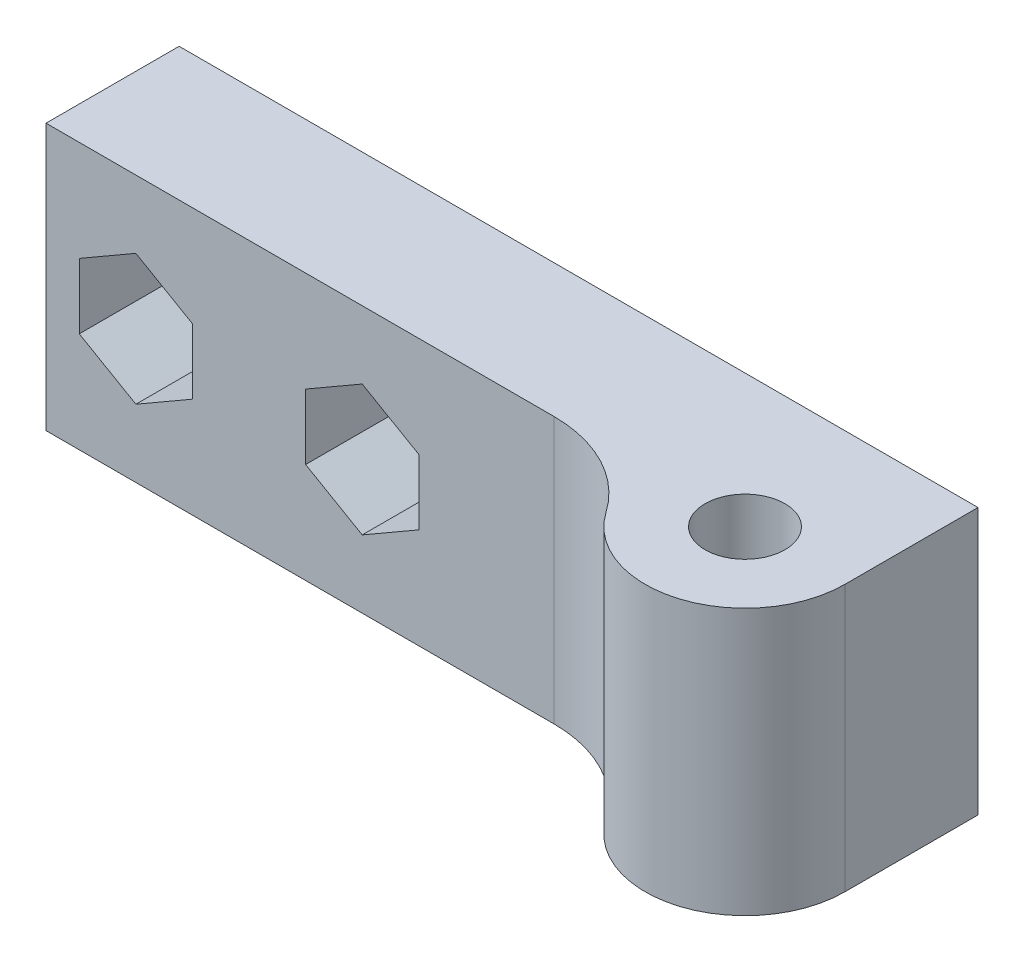
SolidWorks part; units mm, degrees
ref_plane "Front Plane" through (0, 0, 0) normal (0, 0, 1) x (1, 0, 0)
ref_plane "Top Plane" through (0, 0, 0) normal (0, 1, 0) x (1, 0, 0)
ref_plane "Right Plane" through (0, 0, 0) normal (1, 0, 0) x (0, 0, -1)
sketch "Sketch1" plane through (0, 0, 0) normal (0, 0, 1) x (1, 0, 0)
  line L1 (-30, 0) -> (30, 0)
  line L2 (-30, 0) -> (-30, -20)
  line L3 (-30, -20) -> (30, -20)
  line L4 (30, 0) -> (30, -20)
  point P4 (0, 0)
  dimension "D1" = 60
  dimension "D2" = 20
extrude "Boss-Extrude1" add sketch "Sketch1" along normal blind 10
sketch "Sketch2" plane through (0, 0, 10) normal (0, 0, 1) x (1, 0, 0)
  line L0 (-30, -10) -> (-23.25, -10) construction
  line L1 (-23.25, -14.9075) -> (-19, -12.4537)
  line L2 (-19, -12.4537) -> (-19, -7.5463)
  line L3 (-19, -7.5463) -> (-23.25, -5.0925)
  line L4 (-23.25, -5.0925) -> (-27.5, -7.5463)
  line L5 (-27.5, -7.5463) -> (-27.5, -12.4537)
  line L6 (-27.5, -12.4537) -> (-23.25, -14.9075)
  line L7 (-30, 0) -> (-30, -20) construction
  line L8 (-23.25, -5.0925) -> (-23.25, -10) construction
  circle A0 centre (-23.25, -10) radius 4.25 construction
  dimension "D1" = 8.5
  dimension "D2" = 2.5
extrude "Cut-Extrude1" cut sketch "Sketch2" against normal blind 7.5
sketch "Sketch5" plane through (0, 0, 2.5) normal (0, 0, 1) x (1, 0, 0)
  line L0 (-23.25, -5.0925) -> (-23.25, -14.9075) construction
  circle A0 centre (-23.25, -10) radius 2.75
  dimension "D1" = 5.5
extrude "Cut-Extrude3" cut sketch "Sketch5" against normal through all
pattern_linear "LPattern1" count 2 spacing 17 along (1, 0, 0) of "Cut-Extrude3", "Cut-Extrude1"
sketch "Sketch3" plane through (0, 0, 0) normal (0, 1, 0) x (1, 0, 0)
  line L1 (30, -10) -> (30, 0) construction
  line L2 (30, -10) -> (-30, -10) construction
  circle A0 centre (22.5, -10) radius 7.5
  dimension "D1" = 15
extrude "Boss-Extrude2" add sketch "Sketch3" against normal through all
sketch "Sketch4" plane through (0, 0, 0) normal (0, 1, 0) x (1, 0, 0)
  circle A0 centre (22.5, -10) radius 3
  arc A1 (15, -10) -> (30, -10) centre (22.5, -10) ccw construction
  dimension "D1" = 6
extrude "Cut-Extrude2" cut sketch "Sketch4" against normal through all
fillet "Fillet1" radius 10 1 edges at (15, -10, 10)
